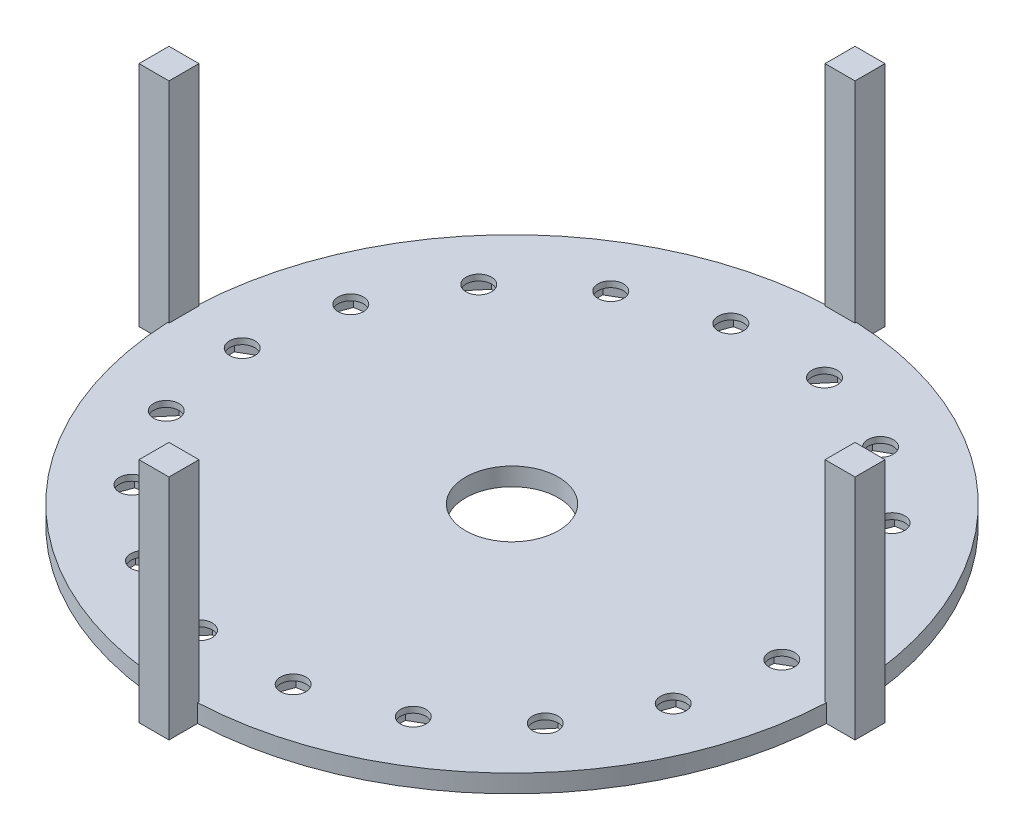
SolidWorks part; units mm, degrees
material "ABS"
ref_plane "Front Plane" through (0, 0, 0) normal (0, 0, 1) x (1, 0, 0)
ref_plane "Top Plane" through (0, 0, 0) normal (0, 1, 0) x (1, 0, 0)
ref_plane "Right Plane" through (0, 0, 0) normal (1, 0, 0) x (0, 0, -1)
sketch "Sketch1" plane through (0, 0, 0) normal (0, 1, 0) x (1, 0, 0)
  line L0 (0, 0) -> (-110, 0) construction
  circle A0 centre (0, 0) radius 110
  circle A1 centre (-90, 0) radius 4.25
  circle A2 centre (-84.5723, 30.7818) radius 4.25
  circle A3 centre (-68.944, 57.8509) radius 4.25
  circle A4 centre (-45, 77.9423) radius 4.25
  circle A5 centre (-15.6283, 88.6327) radius 4.25
  circle A6 centre (15.6283, 88.6327) radius 4.25
  circle A7 centre (45, 77.9423) radius 4.25
  circle A8 centre (68.944, 57.8509) radius 4.25
  circle A9 centre (84.5723, 30.7818) radius 4.25
  circle A10 centre (90, 0) radius 4.25
  circle A11 centre (84.5723, -30.7818) radius 4.25
  circle A12 centre (68.944, -57.8509) radius 4.25
  circle A13 centre (45, -77.9423) radius 4.25
  circle A14 centre (15.6283, -88.6327) radius 4.25
  circle A15 centre (-15.6283, -88.6327) radius 4.25
  circle A16 centre (-45, -77.9423) radius 4.25
  circle A17 centre (-68.944, -57.8509) radius 4.25
  circle A18 centre (-84.5723, -30.7818) radius 4.25
  circle A19 centre (0, 0) radius 15.5
  point P43 (0, 0)
  dimension "D1" = 220
  dimension "D2" = 8.5
  dimension "D5" = 31
  dimension "D3" = 90
  dimension "D4" = 18
extrude "Boss-Extrude1" add sketch "Sketch1" along normal blind 6
sketch "Sketch2" plane through (0, 6, 0) normal (0, 1, 0) x (1, 0, 0)
  line L1 (-87.0349, 24.016) -> (-79.9443, 25.2663)
  line L2 (-90, -7.2) -> (-83.7646, -3.6)
  line L3 (-83.7646, -3.6) -> (-83.7646, 3.6)
  line L4 (-83.7646, 3.6) -> (-90, 7.2)
  line L5 (-90, 7.2) -> (-96.2354, 3.6)
  line L6 (-96.2354, 3.6) -> (-96.2354, -3.6)
  line L7 (-96.2354, -3.6) -> (-90, -7.2)
  line L8 (-79.9443, 25.2663) -> (-77.4817, 32.0321)
  line L9 (-77.4817, 32.0321) -> (-82.1098, 37.5476)
  line L10 (-82.1098, 37.5476) -> (-89.2004, 36.2973)
  line L11 (-89.2004, 36.2973) -> (-91.663, 29.5315)
  line L12 (-91.663, 29.5315) -> (-87.0349, 24.016)
  line L13 (-73.5721, 52.3354) -> (-66.4815, 51.0851)
  line L14 (-66.4815, 51.0851) -> (-61.8534, 56.6006)
  line L15 (-61.8534, 56.6006) -> (-64.3159, 63.3664)
  line L16 (-64.3159, 63.3664) -> (-71.4065, 64.6167)
  line L17 (-71.4065, 64.6167) -> (-76.0346, 59.1012)
  line L18 (-76.0346, 59.1012) -> (-73.5721, 52.3354)
  line L19 (-51.2354, 74.3423) -> (-45, 70.7423)
  line L20 (-45, 70.7423) -> (-38.7646, 74.3423)
  line L21 (-38.7646, 74.3423) -> (-38.7646, 81.5423)
  line L22 (-38.7646, 81.5423) -> (-45, 85.1423)
  line L23 (-45, 85.1423) -> (-51.2354, 81.5423)
  line L24 (-51.2354, 81.5423) -> (-51.2354, 74.3423)
  line L25 (-22.719, 87.3824) -> (-18.0909, 81.8669)
  line L26 (-18.0909, 81.8669) -> (-11.0003, 83.1172)
  line L27 (-11.0003, 83.1172) -> (-8.5377, 89.883)
  line L28 (-8.5377, 89.883) -> (-13.1658, 95.3985)
  line L29 (-13.1658, 95.3985) -> (-20.2564, 94.1482)
  line L30 (-20.2564, 94.1482) -> (-22.719, 87.3824)
  line L31 (8.5377, 89.883) -> (11.0003, 83.1172)
  line L32 (11.0003, 83.1172) -> (18.0909, 81.8669)
  line L33 (18.0909, 81.8669) -> (22.719, 87.3824)
  line L34 (22.719, 87.3824) -> (20.2564, 94.1482)
  line L35 (20.2564, 94.1482) -> (13.1658, 95.3985)
  line L36 (13.1658, 95.3985) -> (8.5377, 89.883)
  line L37 (38.7646, 81.5423) -> (38.7646, 74.3423)
  line L38 (38.7646, 74.3423) -> (45, 70.7423)
  line L39 (45, 70.7423) -> (51.2354, 74.3423)
  line L40 (51.2354, 74.3423) -> (51.2354, 81.5423)
  line L41 (51.2354, 81.5423) -> (45, 85.1423)
  line L42 (45, 85.1423) -> (38.7646, 81.5423)
  line L43 (64.3159, 63.3664) -> (61.8534, 56.6006)
  line L44 (61.8534, 56.6006) -> (66.4815, 51.0851)
  line L45 (66.4815, 51.0851) -> (73.5721, 52.3354)
  line L46 (73.5721, 52.3354) -> (76.0346, 59.1012)
  line L47 (76.0346, 59.1012) -> (71.4065, 64.6167)
  line L48 (71.4065, 64.6167) -> (64.3159, 63.3664)
  line L49 (82.1098, 37.5476) -> (77.4817, 32.0321)
  line L50 (77.4817, 32.0321) -> (79.9443, 25.2663)
  line L51 (79.9443, 25.2663) -> (87.0349, 24.016)
  line L52 (87.0349, 24.016) -> (91.663, 29.5315)
  line L53 (91.663, 29.5315) -> (89.2004, 36.2973)
  line L54 (89.2004, 36.2973) -> (82.1098, 37.5476)
  line L55 (90, 7.2) -> (83.7646, 3.6)
  line L56 (83.7646, 3.6) -> (83.7646, -3.6)
  line L57 (83.7646, -3.6) -> (90, -7.2)
  line L58 (90, -7.2) -> (96.2354, -3.6)
  line L59 (96.2354, -3.6) -> (96.2354, 3.6)
  line L60 (96.2354, 3.6) -> (90, 7.2)
  line L61 (87.0349, -24.016) -> (79.9443, -25.2663)
  line L62 (79.9443, -25.2663) -> (77.4817, -32.0321)
  line L63 (77.4817, -32.0321) -> (82.1098, -37.5476)
  line L64 (82.1098, -37.5476) -> (89.2004, -36.2973)
  line L65 (89.2004, -36.2973) -> (91.663, -29.5315)
  line L66 (91.663, -29.5315) -> (87.0349, -24.016)
  line L67 (73.5721, -52.3354) -> (66.4815, -51.0851)
  line L68 (66.4815, -51.0851) -> (61.8534, -56.6006)
  line L69 (61.8534, -56.6006) -> (64.3159, -63.3664)
  line L70 (64.3159, -63.3664) -> (71.4065, -64.6167)
  line L71 (71.4065, -64.6167) -> (76.0346, -59.1012)
  line L72 (76.0346, -59.1012) -> (73.5721, -52.3354)
  line L73 (51.2354, -74.3423) -> (45, -70.7423)
  line L74 (45, -70.7423) -> (38.7646, -74.3423)
  line L75 (38.7646, -74.3423) -> (38.7646, -81.5423)
  line L76 (38.7646, -81.5423) -> (45, -85.1423)
  line L77 (45, -85.1423) -> (51.2354, -81.5423)
  line L78 (51.2354, -81.5423) -> (51.2354, -74.3423)
  line L79 (22.719, -87.3824) -> (18.0909, -81.8669)
  line L80 (18.0909, -81.8669) -> (11.0003, -83.1172)
  line L81 (11.0003, -83.1172) -> (8.5377, -89.883)
  line L82 (8.5377, -89.883) -> (13.1658, -95.3985)
  line L83 (13.1658, -95.3985) -> (20.2564, -94.1482)
  line L84 (20.2564, -94.1482) -> (22.719, -87.3824)
  line L85 (-8.5377, -89.883) -> (-11.0003, -83.1172)
  line L86 (-11.0003, -83.1172) -> (-18.0909, -81.8669)
  line L87 (-18.0909, -81.8669) -> (-22.719, -87.3824)
  line L88 (-22.719, -87.3824) -> (-20.2564, -94.1482)
  line L89 (-20.2564, -94.1482) -> (-13.1658, -95.3985)
  line L90 (-13.1658, -95.3985) -> (-8.5377, -89.883)
  line L91 (-38.7646, -81.5423) -> (-38.7646, -74.3423)
  line L92 (-38.7646, -74.3423) -> (-45, -70.7423)
  line L93 (-45, -70.7423) -> (-51.2354, -74.3423)
  line L94 (-51.2354, -74.3423) -> (-51.2354, -81.5423)
  line L95 (-51.2354, -81.5423) -> (-45, -85.1423)
  line L96 (-45, -85.1423) -> (-38.7646, -81.5423)
  line L97 (-64.3159, -63.3664) -> (-61.8534, -56.6006)
  line L98 (-61.8534, -56.6006) -> (-66.4815, -51.0851)
  line L99 (-66.4815, -51.0851) -> (-73.5721, -52.3354)
  line L100 (-73.5721, -52.3354) -> (-76.0346, -59.1012)
  line L101 (-76.0346, -59.1012) -> (-71.4065, -64.6167)
  line L102 (-71.4065, -64.6167) -> (-64.3159, -63.3664)
  line L103 (-82.1098, -37.5476) -> (-77.4817, -32.0321)
  line L104 (-77.4817, -32.0321) -> (-79.9443, -25.2663)
  line L105 (-79.9443, -25.2663) -> (-87.0349, -24.016)
  line L106 (-87.0349, -24.016) -> (-91.663, -29.5315)
  line L107 (-91.663, -29.5315) -> (-89.2004, -36.2973)
  line L108 (-89.2004, -36.2973) -> (-82.1098, -37.5476)
  line L241 (-90, 7.2) -> (-90, -7.2) construction
  circle A0 centre (0, 0) radius 90 construction
  circle A1 centre (-90, 0) radius 6.2354 construction
  dimension "D1" = 180
  dimension "D2" = 14.4
  dimension "D3" = 18
extrude "Cut-Extrude1" cut sketch "Sketch2" against normal blind 6 from offset 2 offset against normal yes
sketch "Sketch4" plane through (0, 6, 0) normal (0, 1, 0) x (1, 0, 0)
  line L0 (-109.4386, 0) -> (110, 0) construction
  line L1 (0, 110) -> (0, -110) construction
  line L6 (-109.4386, -5) -> (-119.4386, -5)
  line L7 (-109.4386, -5) -> (-109.4386, 5)
  line L8 (-109.4386, 5) -> (-119.4386, 5)
  line L9 (-119.4386, -5) -> (-119.4386, 5)
  line L10 (-109.4386, -5) -> (-119.4386, 5) construction
  line L11 (-109.4386, 5) -> (-119.4386, -5) construction
  line L12 (109.4386, 5) -> (119.4386, 5)
  line L13 (119.4386, -5) -> (119.4386, 5)
  line L14 (109.4386, -5) -> (119.4386, -5)
  line L15 (109.4386, -5) -> (109.4386, 5)
  line L16 (0, 0) -> (-77.7817, -77.7817) construction
  line L17 (5, -109.4386) -> (5, -119.4386)
  line L18 (-5, -119.4386) -> (5, -119.4386)
  line L19 (-5, -109.4386) -> (-5, -119.4386)
  line L20 (-5, -109.4386) -> (5, -109.4386)
  line L21 (-5, 109.4386) -> (5, 109.4386)
  line L22 (-5, 109.4386) -> (-5, 119.4386)
  line L23 (-5, 119.4386) -> (5, 119.4386)
  line L24 (5, 109.4386) -> (5, 119.4386)
  circle A0 centre (0, 0) radius 110 construction
  point P5 (-114.4386, 0)
  point P10 (-109.4386, 0)
  dimension "D1" = 10
  dimension "D2" = 10
  dimension "D3" = 45
extrude "Boss-Extrude3" add sketch "Sketch4" along normal blind 70 and the other way up to surface
